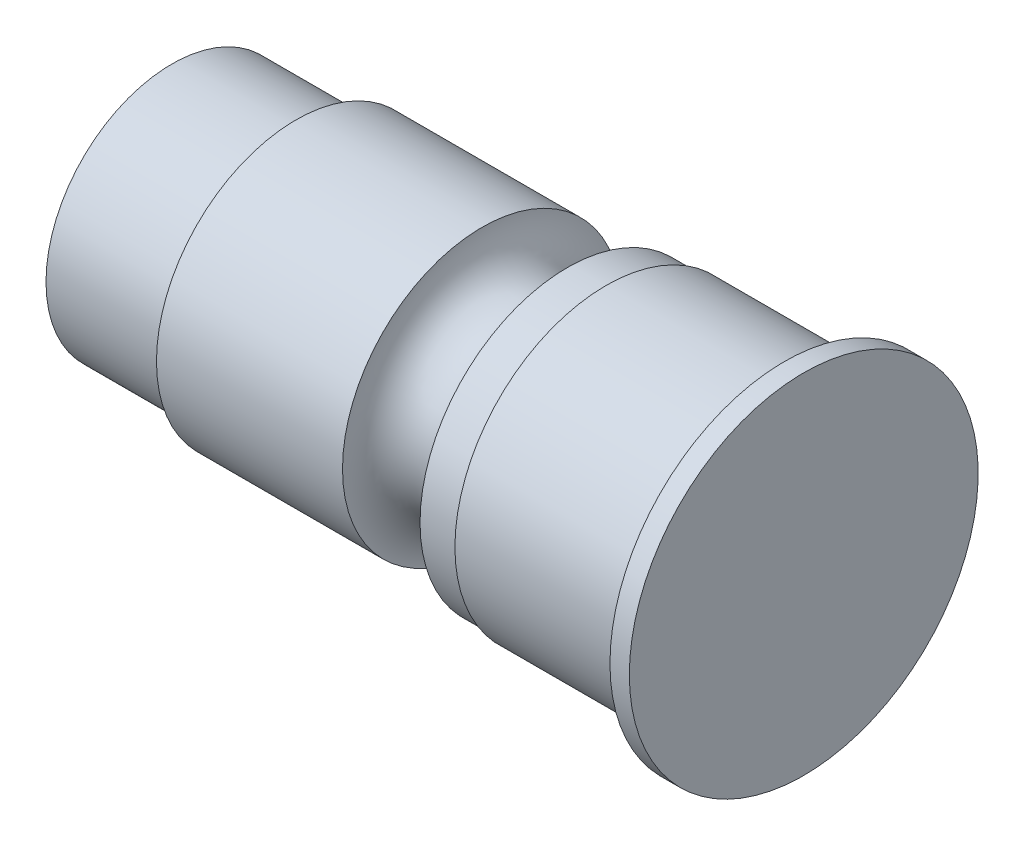
SolidWorks part; units mm, degrees
ref_plane "Front Plane" through (0, 0, 0) normal (1, 0, 0) x (0, 1, 0)
ref_plane "Top Plane" through (0, 0, 0) normal (0, 0, 1) x (0, 1, 0)
ref_plane "Right Plane" through (0, 0, 0) normal (0, 1, 0) x (-1, 0, 0)
sketch "Sketch1" plane through (0, 0, 0) normal (0, 1, 0) x (-1, 0, 0)
  line L0 (0, 0) -> (0, 45)
  line L1 (0, 45) -> (5, 45)
  line L2 (5, 45) -> (5, 39)
  line L3 (5, 39) -> (51, 39)
  line L4 (51, 39) -> (51, 38)
  line L7 (51, 38) -> (61, 38)
  line L8 (61, 38) -> (61, 36)
  line L9 (83, 36) -> (131, 36)
  line L10 (131, 36) -> (131, 32.5)
  line L11 (131, 32.5) -> (163, 32.5)
  line L12 (163, 32.5) -> (163, 0)
  line L13 (163, 0) -> (0, 0)
  arc A0 (61, 36) -> (83, 36) centre (72, 36) ccw
  point P15 (61.9839, 29.1925)
  point P16 (61.9839, 24.174)
  dimension "D10" = 11
  dimension "D1" = 45
  dimension "D2" = 5
  dimension "D3" = 163
  dimension "D4" = 32
  dimension "D5" = 80
  dimension "D6" = 39
  dimension "D7" = 112
  dimension "D8" = 102
  dimension "D9" = 38
  dimension "D11" = 36
  dimension "D12" = 32.5
revolve "Revolve1" add sketch "Sketch1" angle 360 about L13
